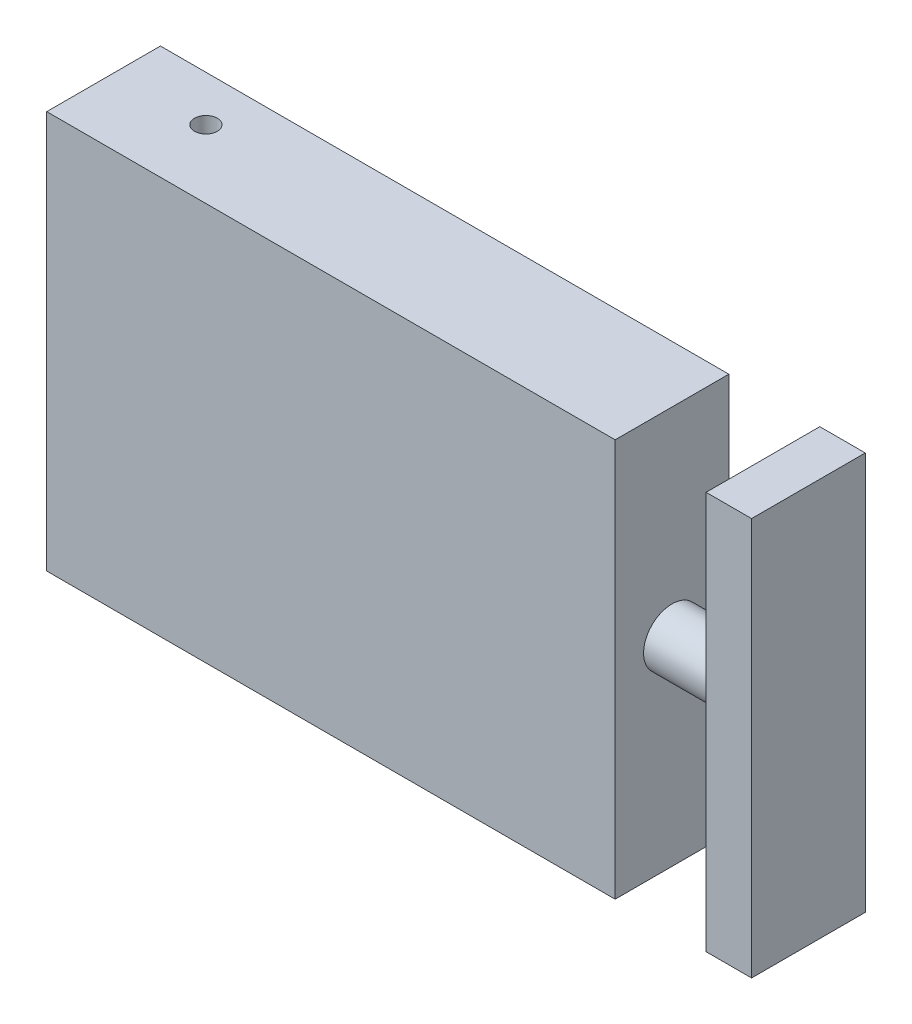
SolidWorks part; units mm, degrees
ref_plane "Front Plane" through (0, 0, 0) normal (0, 0, 1) x (1, 0, 0)
ref_plane "Top Plane" through (0, 0, 0) normal (0, 1, 0) x (1, 0, 0)
ref_plane "Right Plane" through (0, 0, 0) normal (1, 0, 0) x (0, 0, -1)
sketch "Sketch1" plane through (0, 0, 0) normal (0, 0, 1) x (1, 0, 0)
  line L1 (0, 0) -> (500, 0)
  line L2 (0, 0) -> (0, -350)
  line L3 (0, -350) -> (500, -350)
  line L4 (500, 0) -> (500, -350)
  dimension "D1" = 500
  dimension "D2" = 350
extrude "Boss-Extrude1" add sketch "Sketch1" along normal blind 100
sketch "Sketch2" plane through (0, -350, 0) normal (0, -1, 0) x (1, 0, 0)
  line L0 (0, 100) -> (0, 0) construction
  line L1 (0, 0) -> (500, 0) construction
  circle A0 centre (80, 40) radius 10
  dimension "D1" = 20
  dimension "D2" = 80
  dimension "D3" = 40
extrude "Cut-Extrude1" cut sketch "Sketch2" against normal through all
sketch "Sketch3" plane through (0, 0, 0) normal (0, 0, -1) x (-1, 0, 0)
  line L0 (-80, -350) -> (-80, 0) construction
  line L1 (0, -350) -> (-500, -350) construction
  line L2 (-500, 0) -> (0, 0) construction
  line L3 (-500, -175) -> (0, -175) construction
  line L4 (-500, -350) -> (-500, 0) construction
  line L5 (0, 0) -> (0, -350) construction
  line L6 (-380, -350) -> (-380, 0) construction
  line L7 (-440, -175) -> (-320, -175)
  arc A0 (-440, -175) -> (-320, -175) centre (-380, -175) ccw
  dimension "D3" = 60
  dimension "D1" = 80
  dimension "D2" = 120
revolve "Revolve1" add sketch "Sketch3" angle 180 about L3
sketch "Sketch4" plane through (500, 0, 0) normal (1, 0, 0) x (0, 0, -1)
  line L0 (0, -350) -> (0, 0) construction
  circle A0 centre (-50, -175) radius 25
  point P4 (0, -175)
  dimension "D1" = 50
extrude "Boss-Extrude2" add sketch "Sketch4" along normal blind 80
sketch "Sketch5" plane through (580, 0, 0) normal (1, 0, 0) x (0, 0, -1)
  line L1 (0, -350) -> (-100, -350)
  line L2 (0, -350) -> (0, 0)
  line L3 (0, 0) -> (-100, 0)
  line L4 (-100, -350) -> (-100, 0)
  line L5 (0, -350) -> (-100, 0) construction
  line L6 (0, 0) -> (-100, -350) construction
  point P0 (-50, -175)
extrude "Boss-Extrude3" add sketch "Sketch5" along normal blind 40
sketch "Sketch6" plane through (0, 0, 0) normal (0, 0, -1) x (-1, 0, 0)
  line L0 (-250, -350) -> (-250, 0) construction
  line L1 (0, -350) -> (-500, -350) construction
  line L2 (-500, 0) -> (0, 0) construction
  line L3 (0, -175) -> (-500, -175) construction
  line L4 (0, 0) -> (0, -350) construction
  line L5 (-500, -350) -> (-500, 0) construction
  point P12 (-250, -175)
